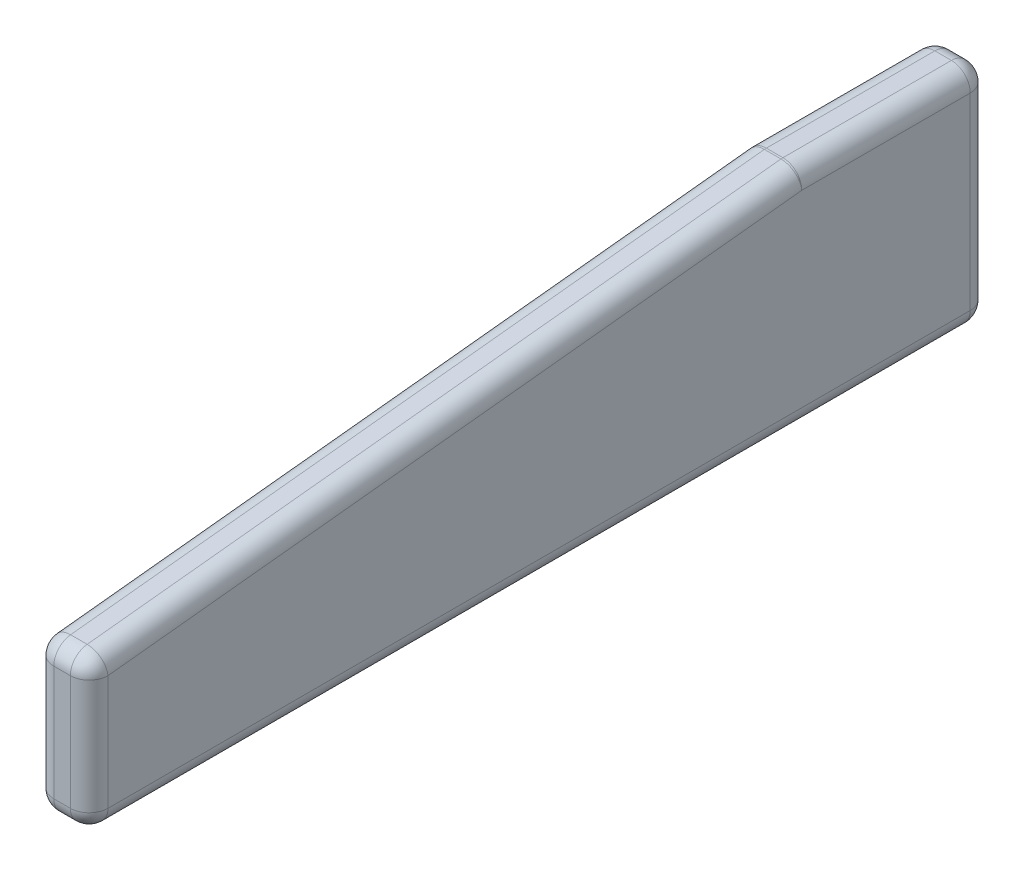
SolidWorks part; units mm, degrees
ref_plane "Front Plane" through (0, 0, 0) normal (0, 0, 1) x (1, 0, 0)
ref_plane "Top Plane" through (0, 0, 0) normal (0, 1, 0) x (1, 0, 0)
ref_plane "Right Plane" through (0, 0, 0) normal (1, 0, 0) x (0, 0, -1)
sketch "Sketch1" plane through (0, 0, 0) normal (1, 0, 0) x (0, 0, -1)
  line L0 (0, 0) -> (0, 84.1309) construction
  line L1 (0, 0) -> (161.7203, 0) construction
  line L2 (-166.9735, -57.6462) -> (123.786, -57.6462)
  line L3 (130.136, -51.2962) -> (130.136, 12.2038)
  line L4 (123.786, 18.5538) -> (66.9711, 18.5538)
  line L5 (66.3027, 18.5185) -> (-167.6419, -6.2448)
  line L6 (-173.3235, -12.5596) -> (-173.3235, -51.2962)
  arc A0 (66.3027, 18.5185) -> (66.9711, 18.5538) centre (66.9711, 12.2038) cw
  arc A1 (123.786, 18.5538) -> (130.136, 12.2038) centre (123.786, 12.2038) cw
  arc A2 (130.136, -51.2962) -> (123.786, -57.6462) centre (123.786, -51.2962) cw
  arc A3 (-166.9735, -57.6462) -> (-173.3235, -51.2962) centre (-166.9735, -51.2962) cw
  arc A4 (-173.3235, -12.5596) -> (-167.6419, -6.2448) centre (-166.9735, -12.5596) cw
  point P11 (66.636, 18.5538)
  point P14 (130.136, 18.5538)
  point P17 (130.136, -57.6462)
  point P20 (-173.3235, -57.6462)
  point P23 (-173.3235, -6.8462)
  dimension "D5" = 6.35
  dimension "D1" = 241.3
  dimension "D2" = 63.5
  dimension "D3" = 76.2
  dimension "D4" = 50.8
extrude "Boss-Extrude1" add sketch "Sketch1" along normal blind 18.288
fillet "Fillet1" radius 6.35 20 edges at (0, 16.6939, -128.2761) (0, -19.5462, -130.136) (0, -55.7864, -128.2761) (0, -57.6462, 21.5938) (0, -55.7864, 171.4636) (0, -31.9279, 173.3235) (0, -8.3123, 171.694) (0, 6.1368, 50.6696) (0, 18.5449, -66.6364) (18.288, 18.5449, -66.6364) (18.288, 18.5538, -95.3785) (18.288, 16.6939, -128.2761) (18.288, -19.5462, -130.136) (18.288, -55.7864, -128.2761) (18.288, -57.6462, 21.5938) (18.288, -55.7864, 171.4636) (18.288, -31.9279, 173.3235) (18.288, -8.3123, 171.694) (0, 18.5538, -95.3785) (18.288, 6.1368, 50.6696)
